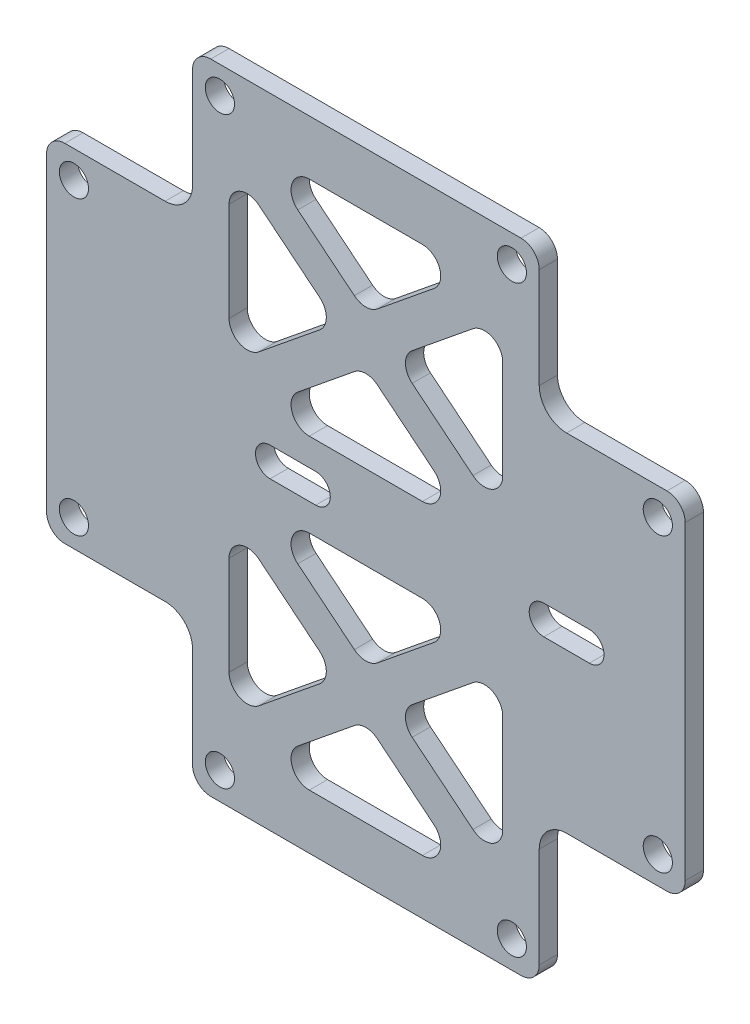
SolidWorks part; units mm, degrees
material "E-玻璃纤维"
ref_plane "前视基准面" through (0, 0, 0) normal (0, 0, 1) x (1, 0, 0)
ref_plane "上视基准面" through (0, 0, 0) normal (0, 1, 0) x (1, 0, 0)
ref_plane "右视基准面" through (0, 0, 0) normal (1, 0, 0) x (0, 0, -1)
sketch "草图1" plane through (0, 0, 0) normal (0, 0, 1) x (1, 0, 0)
  line L1 (-19, -35) -> (19, -35)
  line L2 (-19, -35) -> (-19, 35)
  line L3 (-19, 35) -> (19, 35)
  line L4 (19, -35) -> (19, 35)
  line L5 (0, 35) -> (0, -35) construction
  line L6 (-19, 0) -> (19, 0) construction
  line L7 (-16, -32) -> (16, -32) construction
  line L8 (-16, -32) -> (-16, 32) construction
  line L9 (-16, 32) -> (16, 32) construction
  line L10 (16, -32) -> (16, 32) construction
  line L11 (0, 32) -> (0, -32) construction
  line L12 (-16, 0) -> (16, 0) construction
  circle A0 centre (16, 32) radius 1.6
  circle A1 centre (-16, 32) radius 1.6
  circle A2 centre (-16, -32) radius 1.6
  circle A3 centre (16, -32) radius 1.6
  point P0 (0, 0)
  point P4 (0, 0)
  dimension "D2" = 3.2
  dimension "D1" = 38
  dimension "D3" = 32
  dimension "D4" = 64
  dimension "D5" = 3
extrude "凸台-拉伸1" add sketch "草图1" along normal blind 2
fillet "圆角1" radius 2 4 edges at (19, -35, 1) (-19, -35, 1) (-19, 35, 1) (19, 35, 1)
sketch "草图3" plane through (0, 0, 2) normal (0, 0, 1) x (1, 0, 0)
  line L1 (-35, -19) -> (35, -19)
  line L2 (-35, -19) -> (-35, 19)
  line L3 (-35, 19) -> (35, 19)
  line L4 (35, -19) -> (35, 19)
  line L5 (0, 19) -> (0, -19) construction
  line L6 (-35, 0) -> (35, 0) construction
  line L7 (-32, -16) -> (32, -16) construction
  line L8 (-32, -16) -> (-32, 16) construction
  line L9 (-32, 16) -> (32, 16) construction
  line L10 (32, -16) -> (32, 16) construction
  line L11 (0, 16) -> (0, -16) construction
  line L12 (-32, 0) -> (32, 0) construction
  circle A0 centre (32, 16) radius 1.6
  circle A1 centre (-32, 16) radius 1.6
  circle A2 centre (-32, -16) radius 1.6
  circle A3 centre (32, -16) radius 1.6
  point P0 (0, 0)
  point P4 (0, 0)
  dimension "D5" = 3.2
  dimension "D1" = 38
  dimension "D2" = 70
  dimension "D3" = 32
  dimension "D4" = 64
extrude "凸台-拉伸2" add sketch "草图3" against normal up to surface (2 mm away) contours L2 L1 L4 L3
sketch "草图4" plane through (0, 0, 2) normal (0, 0, 1) x (1, 0, 0)
  line L0 (-10.5, 0) -> (-5.5, 0) construction
  line L1 (-10.5, 1.6) -> (-5.5, 1.6)
  line L2 (-10.5, -1.6) -> (-5.5, -1.6)
  line L3 (19.5, 0) -> (24.5, 0) construction
  line L4 (19.5, 1.6) -> (24.5, 1.6)
  line L5 (19.5, -1.6) -> (24.5, -1.6)
  circle A0 centre (22, 0) radius 1.5 construction
  circle A1 centre (-8, 0) radius 1.5 construction
  circle A2 centre (22, 0) radius 1.5 construction
  circle A3 centre (-8, 0) radius 1.5 construction
  arc A4 (-10.5, 1.6) -> (-10.5, -1.6) centre (-10.5, 0) ccw
  arc A5 (-5.5, -1.6) -> (-5.5, 1.6) centre (-5.5, 0) ccw
  arc A6 (19.5, 1.6) -> (19.5, -1.6) centre (19.5, 0) ccw
  arc A7 (24.5, -1.6) -> (24.5, 1.6) centre (24.5, 0) ccw
  point P8 (-8, 0)
  point P15 (22, 0)
  dimension "D3" = 1.6
  dimension "D1" = 5
  dimension "D2" = 5
extrude "切除-拉伸2" cut sketch "草图4" against normal blind 2
fillet "圆角3" radius 2 4 edges at (35, 19, 1) (35, -19, 1) (-35, -19, 1) (-35, 19, 1)
fillet "圆角4" radius 3 4 edges at (19, -19, 1) (-19, -19, 1) (-19, 19, 1) (19, 19, 1)
sketch "草图5" plane through (0, 0, 2) normal (0, 0, 1) x (1, 0, 0)
  line L0 (-5.5, 1.6) -> (-10.5, 1.6) construction
  line L1 (-15, 4.6) -> (15, 4.6)
  line L2 (-15, 4.6) -> (-15, 29)
  line L3 (-15, 29) -> (15, 29)
  line L4 (15, 4.6) -> (15, 29)
  line L5 (0, 29) -> (0, 4.6) construction
  line L6 (-15, 16.8) -> (15, 16.8) construction
  line L12 (-16.262, 27.4484) -> (13.738, 3.0484)
  line L13 (13.738, 30.5516) -> (-16.262, 6.1516)
  line L14 (-15, 29) -> (15, 4.6) construction
  line L15 (15, 29) -> (-15, 4.6) construction
  line L16 (-13.738, 30.5516) -> (16.262, 6.1516)
  line L17 (16.262, 27.4484) -> (-13.738, 3.0484)
  circle A0 centre (16, 32) radius 1.6 construction
  point P0 (0, 16.8)
  dimension "D1" = 30
  dimension "D2" = 3
  dimension "D3" = 3
  dimension "D4" = 2
  dimension "D5" = 2
extrude "切除-拉伸3" cut sketch "草图5" against normal blind 2 contours L12 L17 L1 | L13 L12 L2 | L3 L16 L13 | L4 L17 L16
mirror "镜向1" about plane through (0, 0, 0) normal (0, 1, 0) of "切除-拉伸3"
fillet "圆角5" radius 2 24 edges at (3.1697, -16.8, 1) (15, -7.178, 1) (15, -26.422, 1) (0, 19.378, 1) (-11.8303, 29, 1) (11.8303, 29, 1) (-15, 26.422, 1) (-3.1697, 16.8, 1) (-15, 7.178, 1) (-11.8303, 4.6, 1) (0, 14.222, 1) (11.8303, 4.6, 1) (15, 7.178, 1) (3.1697, 16.8, 1) (15, 26.422, 1) (0, -14.222, 1) (-11.8303, -4.6, 1) (11.8303, -4.6, 1) (-15, -26.422, 1) (-11.8303, -29, 1) (0, -19.378, 1) (11.8303, -29, 1) (-3.1697, -16.8, 1) (-15, -7.178, 1)
